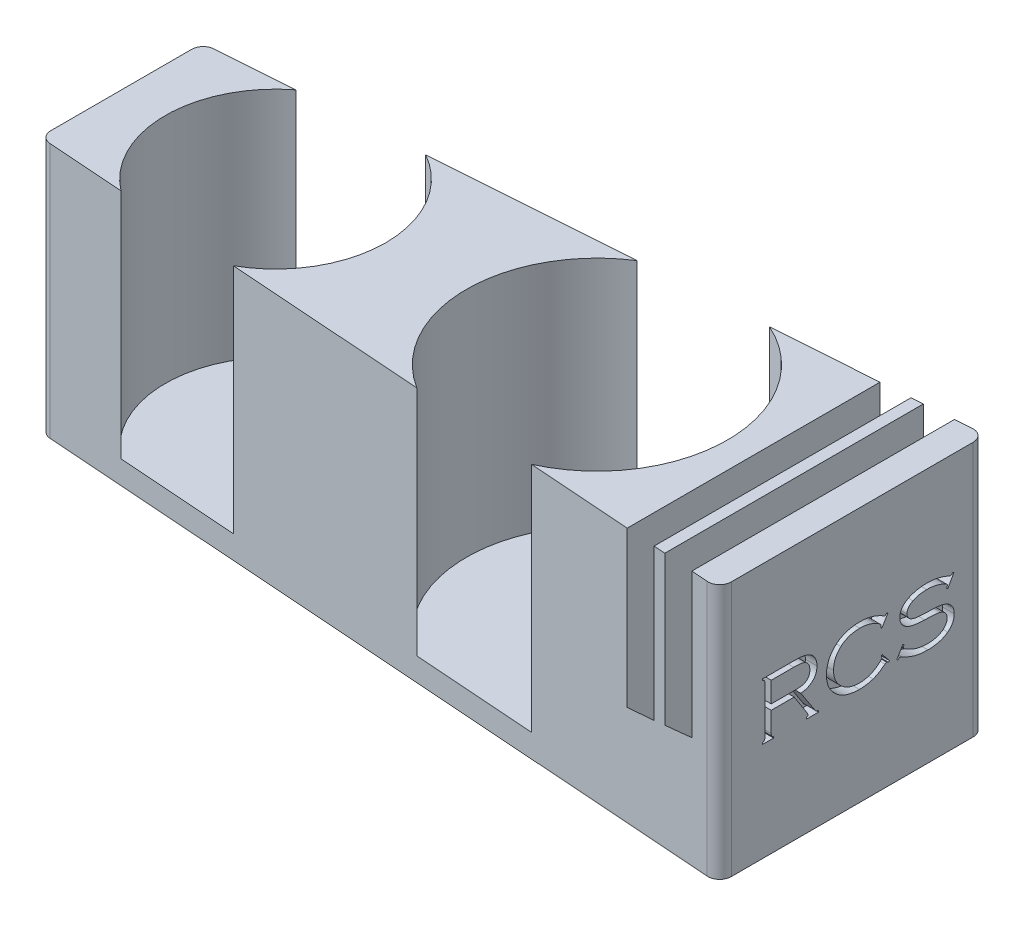
SolidWorks part; units mm, degrees
ref_plane "Front Plane" through (0, 0, 0) normal (0, 0, 1) x (1, 0, 0)
ref_plane "Top Plane" through (0, 0, 0) normal (0, 1, 0) x (1, 0, 0)
ref_plane "Right Plane" through (0, 0, 0) normal (1, 0, 0) x (0, 0, -1)
sketch "Sketch1" plane through (0, 0, 0) normal (0, 1, 0) x (1, 0, 0)
  line L0 (0, 7) -> (63, 11.5)
  line L1 (0, 7) -> (0, -7)
  line L2 (63, 11.5) -> (63, -11.5)
  line L3 (0, -7) -> (63, -11.5)
  line L4 (0, 7) -> (63, -11.5) construction
  line L5 (63, 11.5) -> (0, -7) construction
extrude "Boss-Extrude1" add sketch "Sketch1" along normal blind 2
sketch "Sketch2" plane through (0, 2, 0) normal (0, 1, 0) x (1, 0, 0)
  line L0 (60.4974, 11.3212) -> (60.4974, -11.3212)
  line L1 (63, 11.5) -> (0, 7) construction
  line L2 (0, -7) -> (63, -11.5) construction
  line L3 (60.4974, -11.3212) -> (63, -11.5)
  line L4 (63, -11.5) -> (63, 11.5)
  line L5 (63, 11.5) -> (60.4974, 11.3212)
extrude "Boss-Extrude2" add sketch "Sketch2" along normal blind 20 contours L0 L3 L4 L5
sketch "Sketch4" plane through (0, 2, 0) normal (0, 1, 0) x (1, 0, 0)
  line L0 (60.4974, -11.3212) -> (60.4974, 11.3212)
  line L1 (0, -7) -> (60.4974, -11.3212) construction
  line L2 (60.4974, 11.3212) -> (0, 7) construction
  line L3 (60.4974, 11.3212) -> (57.9949, 11.1425)
  line L4 (57.9949, 11.1425) -> (57.9949, -11.1425)
  line L5 (57.9949, -11.1425) -> (60.4974, -11.3212)
extrude "Boss-Extrude3" add sketch "Sketch4" along normal blind 20
sketch "Sketch5" plane through (57.9949, 0, 0.0002) normal (-1, 0, 0) x (0, 0, 1)
  circle A0 centre (0, 14.2529) radius 12.25
extrude "Cut-Extrude1" cut sketch "Sketch5" against normal blind 2.5
sketch "Sketch6" plane through (60.4949, 0, 0.0002) normal (-1, 0, 0) x (0, 0, 1)
  line L1 (-11.3212, 9.574) -> (11.3209, 9.574)
  line L2 (-11.3212, 9.574) -> (-11.3212, 22)
  line L3 (-11.3212, 22) -> (11.3209, 22)
  line L4 (11.3209, 9.574) -> (11.3209, 22)
  line L5 (11.3209, 9.5731) -> (11.3209, 18.9326) construction
extrude "Cut-Extrude3" cut sketch "Sketch6" along normal blind 2.5
sketch "Sketch8" plane through (0, 2, 0) normal (0, 1, 0) x (1, 0, 0)
  line L0 (57.9949, 11.1425) -> (57, 11.0714)
  line L1 (57.9949, 11.1425) -> (0, 7) construction
  line L2 (57, 11.0714) -> (57, -11.0714)
  line L3 (0, -7) -> (57.9949, -11.1425) construction
  line L4 (57, -11.0714) -> (57.9949, -11.1425)
  line L5 (57.9949, -11.1425) -> (57.9949, 11.1425)
extrude "Boss-Extrude4" add sketch "Sketch8" along normal blind 20
sketch "Sketch9" plane through (0, 2, 0) normal (0, 1, 0) x (1, 0, 0)
  line L0 (57, 11.0714) -> (54.5026, 10.893)
  line L1 (57, 11.0714) -> (0, 7) construction
  line L2 (54.5026, 10.893) -> (54.5025, -10.893)
  line L3 (0, -7) -> (57, -11.0714) construction
  line L4 (54.5025, -10.893) -> (57, -11.0714)
  line L5 (57, -11.0714) -> (57, 11.0714)
extrude "Boss-Extrude5" add sketch "Sketch9" along normal blind 20
sketch "Sketch10" plane through (54.5026, 0, 0) normal (-1, 0, 0) x (0, 0, 1)
  circle A0 centre (0, 14.224) radius 12.25
extrude "Cut-Extrude4" cut sketch "Sketch10" against normal blind 2.5
sketch "Sketch11" plane through (57.0026, 0, 0.0001) normal (-1, 0, 0) x (0, 0, 1)
  line L0 (-11.0717, 8.9818) -> (-11.0717, 22)
  line L1 (-11.0717, 22) -> (11.0716, 22)
  line L2 (11.0716, 22) -> (11.0716, 8.9816)
  line L3 (11.0716, 8.9816) -> (-11.0717, 8.9818)
  line L4 (10.893, 22) -> (11.1424, 22) construction
extrude "Cut-Extrude5" cut sketch "Sketch11" along normal blind 2.5
sketch "Sketch12" plane through (0, 2, 0) normal (0, 1, 0) x (1, 0, 0)
  line L0 (54.5026, 10.893) -> (0, 7)
  line L1 (0, 7) -> (0, -7)
  line L2 (0, -7) -> (54.5026, -10.893)
  line L3 (54.5026, -10.893) -> (54.5026, 10.893)
  line L5 (54.5026, 10.893) -> (0, 7) construction
extrude "Boss-Extrude6" add sketch "Sketch12" along normal blind 20
sketch "Sketch13" plane through (0, 22, 0) normal (0, 1, 0) x (1, 0, 0)
  circle A0 centre (13.3, 0) radius 9.5
extrude "Cut-Extrude6" cut sketch "Sketch13" against normal blind 20
sketch "Sketch14" plane through (0, 22, 0) normal (0, 1, 0) x (1, 0, 0)
  circle A0 centre (41, 0) radius 11.25
extrude "Cut-Extrude7" cut sketch "Sketch14" against normal blind 20
sketch "Sketch15" plane through (63, 0, 0) normal (1, 0, 0) x (0, 0, -1)
  text T0 "RCS" font "Copperplate Gothic Light" height in points 24
extrude "Cut-Extrude8" cut sketch "Sketch15" against normal blind 1
fillet "Fillet2" radius 1 4 edges at (0, 11, -7) (0, 11, 7) (63, 11, -11.5) (63, 11, 11.5)
